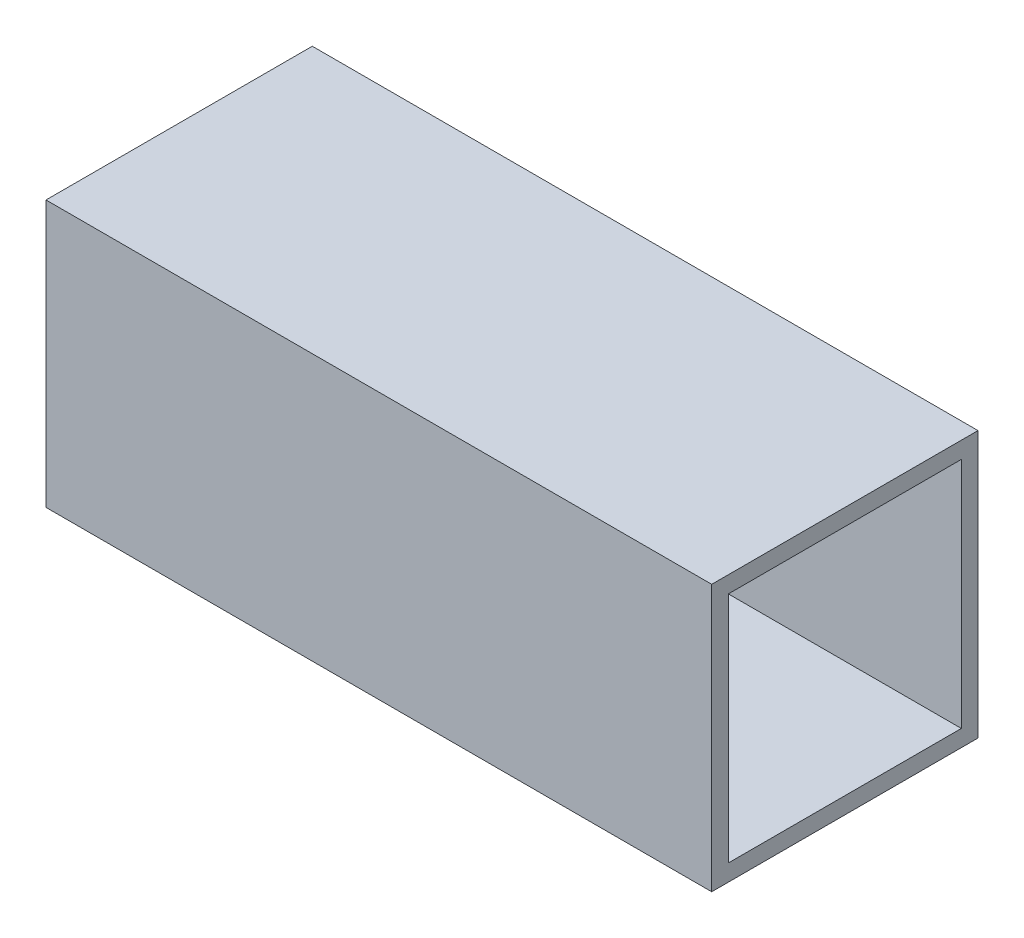
SolidWorks part; units mm, degrees
ref_plane "Front Plane" through (0, 0, 0) normal (0, 0, 1) x (1, 0, 0)
ref_plane "Top Plane" through (0, 0, 0) normal (0, 1, 0) x (1, 0, 0)
ref_plane "Right Plane" through (0, 0, 0) normal (1, 0, 0) x (0, 0, -1)
sketch "Sketch2" plane through (0, 0, 0) normal (1, 0, 0) x (0, 0, -1)
  line L1 (0, 0) -> (40, 0)
  line L2 (0, 0) -> (0, 40)
  line L3 (0, 40) -> (40, 40)
  line L4 (40, 0) -> (40, 40)
  dimension "D1" = 40
extrude "Boss-Extrude1" add sketch "Sketch2" along normal blind 100
shell "Shell1" thickness 2.5
sketch "Sketch3" plane through (0, 0, -40) normal (0, 0, -1) x (-1, 0, 0)
  line L0 (-100, 20) -> (0, 20) construction
  line L1 (-100, 0) -> (-100, 40) construction
  line L2 (0, 0) -> (0, 40) construction
  line L3 (-50, 40) -> (-50, 0) construction
  line L4 (-100, 40) -> (0, 40) construction
  line L5 (-100, 0) -> (0, 0) construction
  circle A0 centre (-50, 20) radius 6
  circle A2 centre (-50, 20) radius 6 construction
extrude "Cut-Extrude1" cut sketch "Sketch3" against normal up to surface (2.5 mm away) up to face at (50, 20, -37.5)
